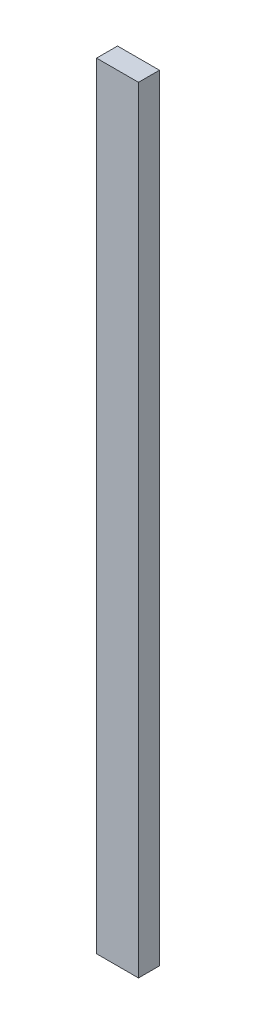
SolidWorks part; units mm, degrees
ref_plane "Front Plane" through (0, 0, 0) normal (0, 0, 1) x (1, 0, 0)
ref_plane "Top Plane" through (0, 0, 0) normal (0, 1, 0) x (1, 0, 0)
ref_plane "Right Plane" through (0, 0, 0) normal (1, 0, 0) x (0, 0, -1)
sketch "Sketch1" plane through (0, 0, 0) normal (0, 0, 1) x (1, 0, 0)
  line L0 (0, 0) -> (20, 0)
  line L1 (20, 0) -> (20, -370)
  line L2 (20, -370) -> (0, -370)
  line L3 (0, -370) -> (0, 0)
  dimension "D1" = 20
  dimension "D2" = 370
extrude "Boss-Extrude1" add sketch "Sketch1" along normal blind 10
